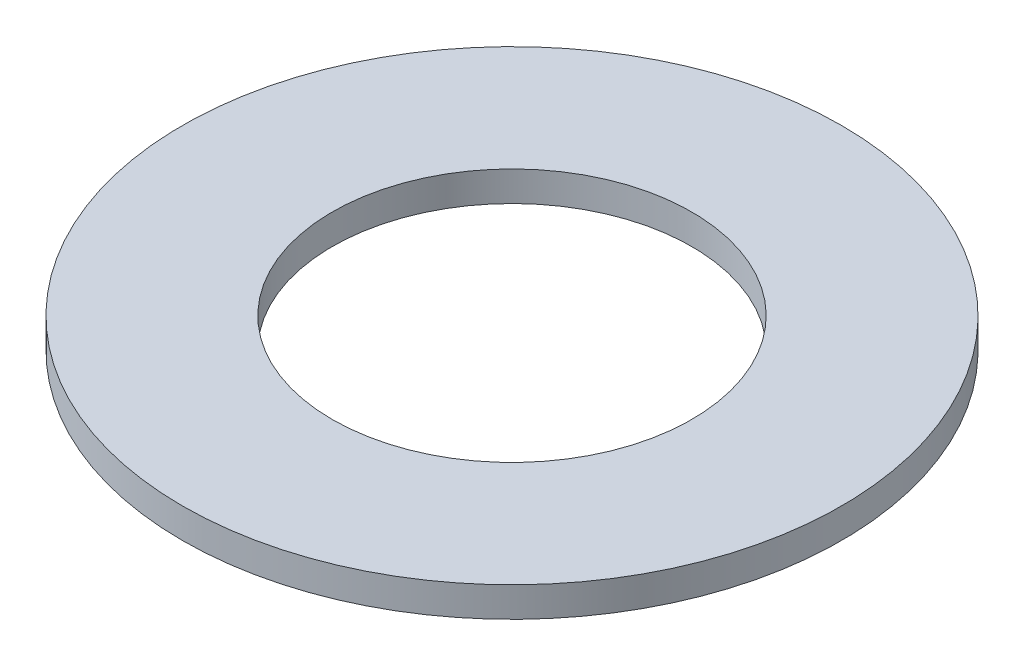
SolidWorks part; units mm, degrees
material "Caoutchouc silicone"
ref_plane "Plan de face" through (0, 0, 0) normal (0, 0, 1) x (1, 0, 0)
ref_plane "Plan de dessus" through (0, 0, 0) normal (0, 1, 0) x (1, 0, 0)
ref_plane "Plan de droite" through (0, 0, 0) normal (1, 0, 0) x (0, 0, -1)
sketch "Esquisse1" plane through (0, 0, 0) normal (0, 1, 0) x (1, 0, 0)
  circle A0 centre (0, 0) radius 5.5
  circle A1 centre (0, 0) radius 3
  dimension "D1" = 11
  dimension "D2" = 6
extrude "Boss.-Extru.1" add sketch "Esquisse1" along normal blind 0.5
